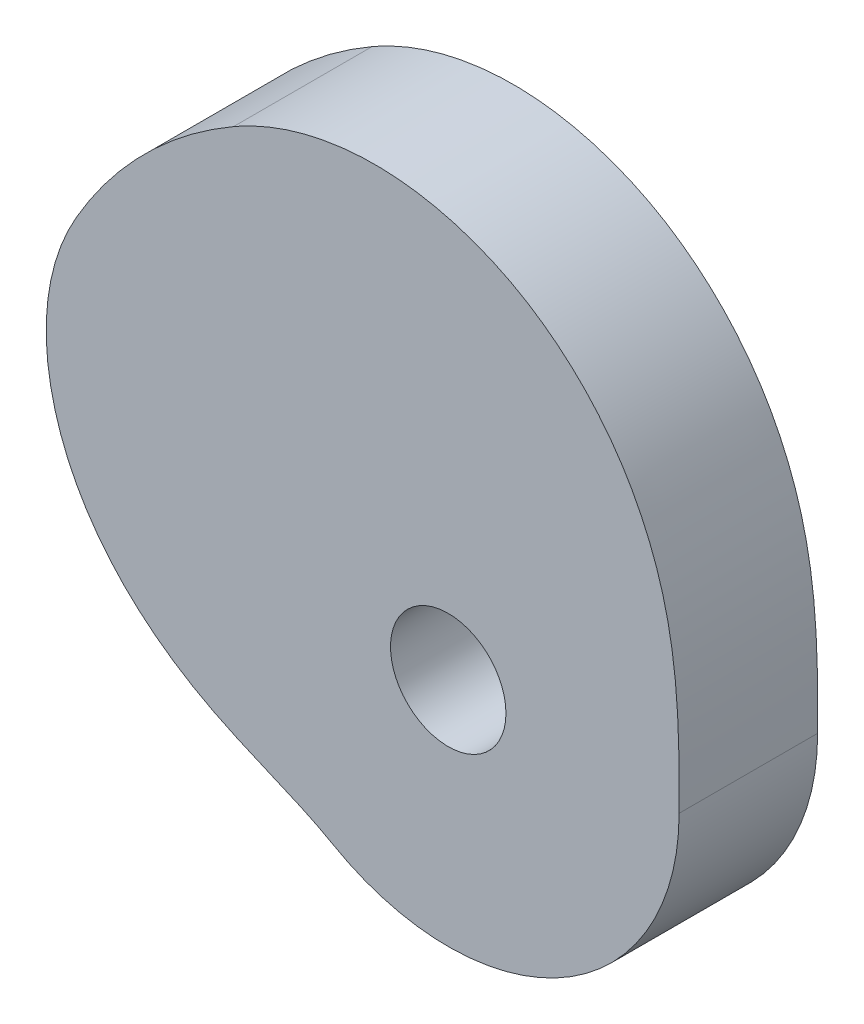
SolidWorks part; units mm, degrees
ref_plane "Front Plane" through (0, 0, 0) normal (0, 0, 1) x (1, 0, 0)
ref_plane "Top Plane" through (0, 0, 0) normal (0, 1, 0) x (1, 0, 0)
ref_plane "Right Plane" through (0, 0, 0) normal (1, 0, 0) x (0, 0, -1)
sketch "Sketch1" plane through (0, 0, 0) normal (0, 0, 1) x (1, 0, 0)
  line L0 (120, 73) -> (120, 30) construction
  line L1 (0, 30) -> (360, 30) construction
  line L2 (0, 30) -> (0, 73) construction
  line L3 (0, 73) -> (360, 73) construction
  line L4 (360, 30) -> (360, 73) construction
  line L5 (150, 73) -> (150, 30) construction
  line L6 (240, 73) -> (240, 30) construction
  line L7 (20, 30) -> (20, 73) construction
  line L8 (40, 30) -> (40, 73) construction
  line L9 (60, 30) -> (60, 73) construction
  line L10 (80, 30) -> (80, 73) construction
  line L11 (100, 30) -> (100, 73) construction
  line L12 (165, 73) -> (165, 30) construction
  line L13 (180, 73) -> (180, 30) construction
  line L14 (195, 73) -> (195, 30) construction
  line L15 (210, 73) -> (210, 30) construction
  line L16 (225, 73) -> (225, 30) construction
  line L17 (0, 51.5) -> (-10.75, 32.8805) construction
  line L18 (0, 51.5) -> (-18.6195, 40.75) construction
  line L19 (0, 51.5) -> (-21.5, 51.5) construction
  line L20 (0, 51.5) -> (-18.6195, 62.25) construction
  line L21 (0, 51.5) -> (-10.75, 70.1195) construction
  line L22 (0, 51.5) -> (0, 73) construction
  line L23 (-10.75, 70.1195) -> (100, 70.1195) construction
  line L24 (-18.6195, 62.25) -> (80, 62.25) construction
  line L25 (-21.5, 51.5) -> (60, 51.5) construction
  line L26 (-18.6195, 40.75) -> (40, 40.75) construction
  line L27 (-10.75, 32.8805) -> (20, 32.8805) construction
  line L28 (120, 73) -> (150, 73)
  line L33 (165, 70.1195) -> (240, 70.1195) construction
  line L34 (180, 62.25) -> (240, 62.25) construction
  line L35 (195, 51.5) -> (240, 51.5) construction
  line L36 (210, 40.75) -> (240, 40.75) construction
  line L37 (225, 32.8805) -> (240, 32.8805) construction
  arc A0 (0, 73) -> (0, 30) centre (0, 51.5) ccw construction
  spline S0 degree 3 poles (0, 30) (14.1712, 29.912) (34.7185, 37.2422) (60, 51.5) (85.2815, 65.7578) (105.8288, 73.088) (120, 73) knots 0 0 0 0 0.323725 0.5 0.676275 1 1 1 1
  spline S1 degree 3 poles (150, 73) (161.1049, 72.9892) (176.6066, 65.3329) (195, 51.5) (213.3934, 37.6671) (228.8951, 30.0108) (240, 30) knots 0 0 0 0 0.317887 0.5 0.682113 1 1 1 1
  point P40 (0, 51.5)
  dimension "D9" = 30
  dimension "D1" = 43
  dimension "D2" = 30
  dimension "D3" = 120
  dimension "D4" = 120
  dimension "D5" = 30
  dimension "D6" = 90
  dimension "D7" = 6
  dimension "D8" = 6
  dimension "D10" = 6
sketch "Sketch2" plane through (0, 0, 0) normal (0, 0, 1) x (1, 0, 0)
  line L0 (0, 0) -> (-25, 43.3013) construction
  line L1 (0, 0) -> (-43.3013, 25) construction
  line L2 (0, 0) -> (-25, -43.3013) construction
  line L3 (0, 0) -> (-50, 0) construction
  line L4 (0, 0) -> (50, 0) construction
  line L5 (0, 0) -> (46.9846, 17.101) construction
  line L6 (0, 0) -> (38.3022, 32.1394) construction
  line L7 (0, 0) -> (25, 43.3013) construction
  line L8 (0, 0) -> (8.6824, 49.2404) construction
  line L9 (0, 0) -> (-8.6824, 49.2404) construction
  line L10 (0, 0) -> (-25, 43.3013) construction
  line L11 (0, 0) -> (-35.3553, -35.3553) construction
  line L12 (0, 0) -> (-43.3013, -25) construction
  line L13 (0, 0) -> (-48.2963, -12.941) construction
  line L14 (0, 0) -> (-50, 0) construction
  line L15 (0, 0) -> (-48.2963, 12.941) construction
  line L16 (0, 0) -> (-43.3013, 25) construction
  line L17 (20, 30) -> (20, 32.8805) construction
  line L18 (40, 30) -> (40, 40.75) construction
  line L19 (60, 30) -> (60, 51.5) construction
  line L20 (80, 30) -> (80, 62.25) construction
  line L21 (100, 30) -> (100, 70.1195) construction
  line L22 (120, 30) -> (120, 73) construction
  line L23 (46.9846, 17.101) -> (49.6914, 18.0862) construction
  line L24 (38.3022, 32.1394) -> (46.5372, 39.0493) construction
  line L25 (25, 43.3013) -> (35.75, 61.9208) construction
  line L26 (8.6824, 49.2404) -> (14.2826, 81.0004) construction
  line L27 (-8.6824, 49.2404) -> (-15.6491, 88.7504) construction
  line L28 (-25, 43.3013) -> (-46.5, 80.5404) construction
  line L29 (150, 30) -> (150, 73) construction
  line L30 (-43.3013, 25) -> (-80.5404, 46.5) construction
  line L31 (165, 30) -> (165, 70.1195) construction
  line L32 (-48.2963, 12.941) -> (-87.0488, 23.3247) construction
  line L33 (180, 30) -> (180, 62.25) construction
  line L34 (0, 30) -> (360, 30) construction
  line L35 (-50, 0) -> (-82.25, 0) construction
  line L36 (195, 30) -> (195, 51.5) construction
  line L37 (-48.2963, -12.941) -> (-69.0637, -18.5056) construction
  line L38 (210, 30) -> (210, 40.75) construction
  line L39 (-43.3013, -25) -> (-52.611, -30.375) construction
  line L40 (225, 30) -> (225, 32.8805) construction
  line L41 (-35.3553, -35.3553) -> (-37.3921, -37.3921) construction
  line L43 (50, 0) -> (55.4524, 5.4524) construction
  line L44 (55.4524, 5.4524) -> (105.4524, 5.4524) construction
  line L45 (105.4524, 5.4524) -> (105.4524, -0.5476) construction
  line L46 (105.4524, -5.4524) -> (105.4524, 0.5476) construction
  line L47 (55.4524, -5.4524) -> (105.4524, -5.4524) construction
  line L48 (50, 0) -> (55.4524, -5.4524) construction
  circle A0 centre (0, 0) radius 50 construction
  arc A1 (-25, -43.3013) -> (50, 0) centre (0, 0) ccw
  circle A2 centre (0, 0) radius 12.5
  circle A3 centre (0, 0) radius 93 construction
  arc A4 (-80.5404, 46.5) -> (-46.5, 80.5404) centre (0, 0) cw
  spline S0 degree 3 poles (50, 0) (50, 5.9744) (50.0602, 19.1535) (47.3363, 40.6297) (36.6056, 63.9257) (14.8378, 83.4794) (-16.0362, 91.5004) (-37.0281, 86.0089) (-46.5, 80.5404) knots 0 0 0 0 0.11585 0.25162 0.413576 0.597519 0.795538 1 1 1 1
  spline S1 degree 3 poles (-80.5404, 46.5) (-84.6777, 39.3339) (-88.9848, 23.5081) (-83.9035, -0.3988) (-70.4573, -18.813) (-53.9324, -30.4108) (-38.3137, -36.9705) (-28.97, -41.0092) (-25, -43.3013) knots 0 0 0 0 0.198314 0.394496 0.581697 0.748831 0.886896 1 1 1 1
  point P17 (0, 0)
  point P23 (0, 0)
  dimension "D1" = 100
  dimension "D9" = 45
  dimension "D2" = 150
  dimension "D3" = 120
  dimension "D4" = 240
  dimension "D5" = 20
  dimension "D7" = 15
  dimension "D8" = 6
  dimension "D10" = 50
  dimension "D11" = 6
  dimension "D6" = 6
extrude "Boss-Extrude1" add sketch "Sketch2" along normal mid plane 30
